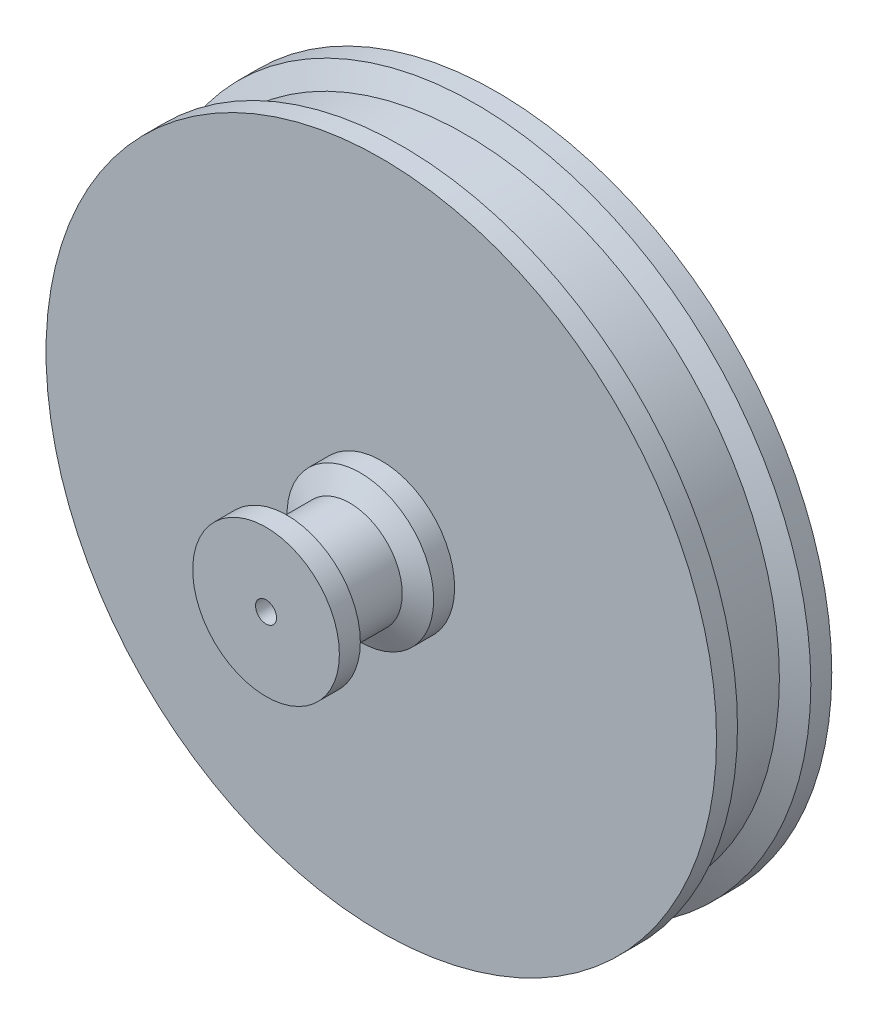
SolidWorks part; units mm, degrees
ref_plane "Front Plane" through (0, 0, 0) normal (0, 0, 1) x (1, 0, 0)
ref_plane "Top Plane" through (0, 0, 0) normal (0, 1, 0) x (1, 0, 0)
ref_plane "Right Plane" through (0, 0, 0) normal (1, 0, 0) x (0, 0, -1)
sketch "Sketch1" plane through (0, 0, 0) normal (0, 0, 1) x (1, 0, 0)
  circle A0 centre (0, 0) radius 32
  circle A1 centre (0, 0) radius 1
  point P4 (0, 0)
  dimension "D1" = 64
  dimension "D2" = 2
extrude "Boss-Extrude1" add sketch "Sketch1" along normal blind 11
sketch "Sketch4" plane through (0, 0, 0) normal (1, 0, 0) x (0, 0, -1)
  line L0 (0, 35.2) -> (0, -35.2) construction
  line L1 (-1000, 0) -> (49000, 0) construction
  line L2 (0, 32) -> (-11, 32) construction
  line L3 (-2, 32) -> (-3, 30)
  line L4 (-3, 30) -> (-8, 30)
  line L5 (-8, 30) -> (-9, 32)
  line L6 (-9, 32) -> (-2, 32)
  line L7 (-5.5, -1000) -> (-5.5, 49000) construction
  line L8 (-11, 32) -> (-11, -32) construction
  point P16 (0, 0)
  point P17 (0, 0)
  dimension "D1" = 5
  dimension "D2" = 2
  dimension "D3" = 5.5
  dimension "D4" = 2
  dimension "D5" = 2
revolve "Cut-Revolve1" cut sketch "Sketch4" angle 360 about L1
sketch "Sketch5" plane through (0, 0, 11) normal (0, 0, 1) x (1, 0, 0)
  circle A0 centre (0, 0) radius 1
  circle A2 centre (0, 0) radius 5
  circle A3 centre (0, 0) radius 1
  dimension "D2" = 10
sketch "Sketch7" plane through (0, 0, 11) normal (0, 0, 1) x (1, 0, 0)
  circle A0 centre (0, 0) radius 1
  circle A1 centre (0, 0) radius 7
  dimension "D1" = 2
  dimension "D2" = 14
extrude "Boss-Extrude3" add sketch "Sketch7" along normal blind 11
sketch "Sketch8" plane through (0, 0, 0) normal (1, 0, 0) x (0, 0, -1)
  line L0 (-16.5, -1000) -> (-16.5, 49000) construction
  line L2 (-22, 7) -> (-22, -7) construction
  line L3 (-20, 7) -> (-13, 7)
  line L4 (-11, 7) -> (-22, 7) construction
  line L5 (-13, 7) -> (-14, 5)
  line L6 (-14, 5) -> (-19, 5)
  line L7 (-19, 5) -> (-20, 7)
  line L8 (-11, 32) -> (-11, -32) construction
  line L9 (-1000, 0) -> (49000, 0) construction
  dimension "D1" = 5.5
  dimension "D2" = 5
  dimension "D3" = 2
  dimension "D4" = 2
  dimension "D5" = 2
revolve "Cut-Revolve3" cut sketch "Sketch8" angle 360 about L9
